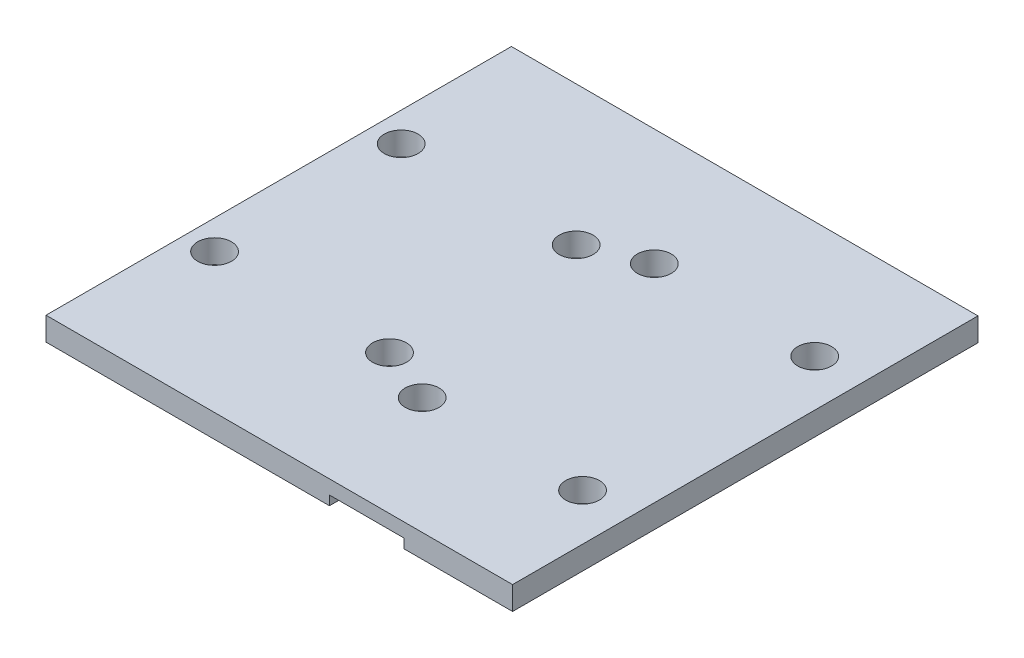
SolidWorks part; units mm, degrees
ref_plane "前视基准面" through (0, 0, 0) normal (0, 0, 1) x (1, 0, 0)
ref_plane "上视基准面" through (0, 0, 0) normal (0, 1, 0) x (1, 0, 0)
ref_plane "右视基准面" through (0, 0, 0) normal (1, 0, 0) x (0, 0, -1)
other "Configuration Table"
sketch "草图1" plane through (0, 0, 0) normal (0, 1, 0) x (1, 0, 0)
  line L1 (0, 0) -> (40, 0)
  line L2 (0, 0) -> (0, 39.9)
  line L3 (0, 39.9) -> (40, 39.9)
  line L4 (40, 0) -> (40, 39.9)
  dimension "D1" = 40
  dimension "D2" = 39.9
extrude "凸台-拉伸1" add sketch "草图1" along normal blind 2
sketch "草图2" plane through (0, 2, 0) normal (0, 1, 0) x (1, 0, 0)
  line L0 (0, 0) -> (2.5, 0) construction
  line L1 (0, 0) -> (40, 0) construction
  line L2 (2.5, 0) -> (2.5, 11.95) construction
  line L3 (2.5, 11.95) -> (17.5, 11.95) construction
  line L4 (17.5, 11.95) -> (17.5, 27.95) construction
  line L5 (17.5, 27.95) -> (2.5, 27.95) construction
  circle A0 centre (2.5, 11.95) radius 1.45
  circle A1 centre (17.5, 11.95) radius 1.45
  circle A2 centre (17.5, 27.95) radius 1.45
  circle A3 centre (2.5, 27.95) radius 1.45
  dimension "D6" = 2.9
  dimension "D1" = 2.5
  dimension "D2" = 11.95
  dimension "D3" = 15
  dimension "D4" = 16
  dimension "D5" = 15
extrude "切除-拉伸1" cut sketch "草图2" against normal blind 2
sketch "草图5" plane through (0, 0, 0) normal (0, -1, 0) x (1, 0, 0)
  line L0 (24.5, -39.9) -> (0, -39.9) construction
  line L1 (40, 0) -> (20, 0) construction
  line L2 (40, 0) -> (40, -39.9) construction
  line L3 (40, -39.9) -> (20, -39.9) construction
  line L4 (20, 0) -> (20, -39.9) construction
  line L6 (20, 0) -> (22.25, 0) construction
  line L9 (22.25, 0) -> (22.25, -10) construction
  line L10 (22.25, -10) -> (36, -10) construction
  line L11 (40, -19.95) -> (-11.1089, -19.95) construction
  circle A0 centre (22.25, -10) radius 1.45
  circle A1 centre (36, -10) radius 1.45
  circle A2 centre (36, -29.9) radius 1.45
  circle A3 centre (22.25, -29.9) radius 1.45
  dimension "D4" = 2.9
  dimension "D6" = 2.9
  dimension "D1" = 20
  dimension "D2" = 2.25
  dimension "D3" = 10
  dimension "D5" = 13.75
extrude "切除-拉伸3" cut sketch "草图5" against normal up to next
sketch "草图7" plane through (0, 0, 0) normal (0, -1, 0) x (1, 0, 0)
  line L0 (40, 0) -> (30.7, 0) construction
  line L1 (0, 0) -> (40, 0) construction
  line L2 (40, -39.9) -> (0, -39.9) construction
  line L3 (30.7, 0) -> (24.3, 0)
  line L4 (30.7, 0) -> (30.7, -39.9)
  line L5 (30.7, -39.9) -> (24.3, -39.9)
  line L6 (24.3, 0) -> (24.3, -39.9)
  dimension "D1" = 9.3
  dimension "D2" = 6.4
extrude "切除-拉伸5" cut sketch "草图7" against normal blind 0.8
